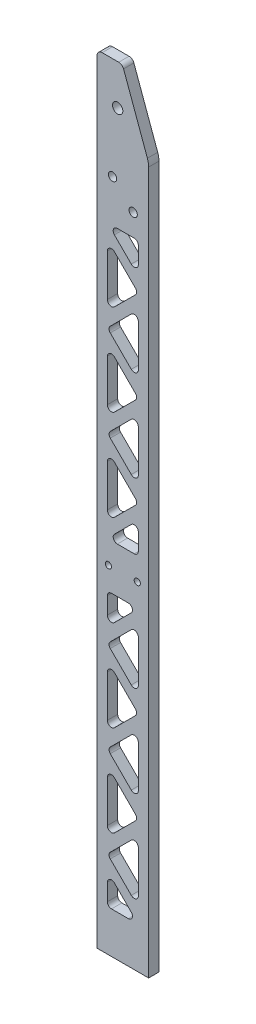
SolidWorks part; units mm, degrees
ref_plane "Plan de face" through (0, 0, 0) normal (0, 0, 1) x (1, 0, 0)
ref_plane "Plan de dessus" through (0, 0, 0) normal (0, 1, 0) x (1, 0, 0)
ref_plane "Plan de droite" through (0, 0, 0) normal (1, 0, 0) x (0, 0, -1)
sketch "Esquisse1" plane through (0, 0, 0) normal (0, 0, 1) x (1, 0, 0)
  line L1 (0, 0) -> (50, 0)
  line L2 (0, 0) -> (0, 594)
  line L3 (0, 594) -> (50, 594)
  line L4 (50, 0) -> (50, 594)
  dimension "D1" = 594
  dimension "D2" = 50
extrude "Boss.-Extru.1" add sketch "Esquisse1" along normal blind 10
sketch "Esquisse2" plane through (0, 0, 10) normal (0, 0, 1) x (1, 0, 0)
  line L0 (10, 10) -> (40, 10)
  line L1 (40, 10) -> (10, 40)
  line L2 (10, 40) -> (10, 10)
  line L3 (0, 0) -> (50, 0) construction
  line L4 (0, 594) -> (0, 0) construction
  line L5 (50, 0) -> (50, 594) construction
  line L6 (40, 24.1421) -> (10, 54.1421)
  line L11 (40, 84.1421) -> (40, 24.1421)
  line L12 (10, 54.1421) -> (40, 54.1421) construction
  line L13 (40, 84.1421) -> (10, 54.1421)
  line L14 (10, 68.2843) -> (10, 128.2843)
  line L15 (40, 98.2843) -> (10, 68.2843)
  line L16 (10, 98.2843) -> (40, 98.2843) construction
  line L17 (40, 98.2843) -> (10, 128.2843)
  line L18 (40, 172.4264) -> (10, 142.4264)
  line L19 (10, 156.5685) -> (10, 216.5685)
  line L20 (40, 186.5685) -> (10, 156.5685)
  line L21 (40, 186.5685) -> (10, 216.5685)
  line L22 (10, 142.4264) -> (40, 142.4264) construction
  line L23 (10, 186.5685) -> (40, 186.5685) construction
  line L24 (40, 172.4264) -> (40, 112.4264)
  line L25 (40, 112.4264) -> (10, 142.4264)
  line L26 (40, 260.7107) -> (10, 230.7107)
  line L28 (40, 274.8528) -> (10, 244.8528)
  line L30 (10, 230.7107) -> (40, 230.7107) construction
  line L31 (10, 274.8528) -> (40, 274.8528)
  line L32 (40, 260.7107) -> (40, 200.7107)
  line L33 (40, 200.7107) -> (10, 230.7107)
  line L34 (40, 348.9949) -> (10, 318.9949)
  line L35 (10, 333.1371) -> (10, 393.1371)
  line L36 (40, 363.1371) -> (10, 333.1371)
  line L37 (40, 363.1371) -> (10, 393.1371)
  line L38 (10, 318.9949) -> (40, 318.9949)
  line L39 (10, 363.1371) -> (40, 363.1371) construction
  line L42 (40, 437.2792) -> (10, 407.2792)
  line L43 (10, 421.4214) -> (10, 481.4214)
  line L44 (40, 451.4214) -> (10, 421.4214)
  line L45 (40, 451.4214) -> (10, 481.4214)
  line L46 (10, 407.2792) -> (40, 407.2792) construction
  line L47 (10, 451.4214) -> (40, 451.4214) construction
  line L48 (40, 437.2792) -> (40, 377.2792)
  line L49 (40, 377.2792) -> (10, 407.2792)
  line L50 (40, 525.5635) -> (10, 495.5635)
  line L51 (10, 509.7056) -> (10, 569.7056)
  line L52 (40, 539.7056) -> (10, 509.7056)
  line L53 (40, 539.7056) -> (10, 569.7056)
  line L54 (10, 495.5635) -> (40, 495.5635) construction
  line L55 (10, 539.7056) -> (40, 539.7056) construction
  line L56 (40, 525.5635) -> (40, 465.5635)
  line L57 (40, 465.5635) -> (10, 495.5635)
  line L62 (10, 583.8478) -> (40, 553.8478)
  line L63 (40, 553.8478) -> (40, 583.8478)
  line L70 (40, 583.8478) -> (10, 583.8478)
  line L71 (10, 244.8528) -> (10, 274.8528)
  line L74 (10, 128.2843) -> (10, 142.4264) construction
  line L75 (40, 98.2843) -> (40, 112.4264) construction
  line L76 (40, 348.9949) -> (40, 318.9949)
  line L77 (10, 244.8528) -> (10, 304.8528) [skipped]
  line L78 (40, 274.8528) -> (10, 304.8528) [skipped]
  line L79 (40, 288.9949) -> (10, 318.9949) [skipped]
  line L80 (40, 348.9949) -> (40, 288.9949) [skipped]
  dimension "D1" = 10
  dimension "D2" = 10
  dimension "D3" = 10
  dimension "D4" = 10
  dimension "D5" = 6
  dimension "D6" = 10
  dimension "D7" = 10
extrude "Enlèv. mat.-Extru.1" cut sketch "Esquisse2" against normal through all both and the other way through all
fillet "Congé1" radius 4 42 edges at (10, 128.2843, 5) (40, 98.2843, 5) (10, 68.2843, 5) (40, 24.1421, 5) (40, 84.1421, 5) (10, 54.1421, 5) (10, 40, 5) (40, 10, 5) (10, 10, 5) (10, 583.8478, 5) (40, 583.8478, 5) (40, 553.8478, 5) (10, 569.7056, 5) (40, 539.7056, 5) (10, 509.7056, 5) (40, 525.5635, 5) (10, 495.5635, 5) (40, 465.5635, 5) (40, 451.4214, 5) (10, 481.4214, 5) (10, 421.4214, 5) (40, 437.2792, 5) (40, 377.2792, 5) (10, 407.2792, 5) (40, 363.1371, 5) (10, 393.1371, 5) (10, 333.1371, 5) (40, 260.7107, 5) (10, 230.7107, 5) (40, 200.7107, 5) (10, 216.5685, 5) (40, 186.5685, 5) (10, 156.5685, 5) (40, 172.4264, 5) (10, 142.4264, 5) (40, 112.4264, 5) (10, 274.8528, 5) (10, 244.8528, 5) (40, 274.8528, 5) (40, 318.9949, 5) (40, 348.9949, 5) (10, 318.9949, 5)
sketch "Esquisse3" plane through (0, 0, 10) normal (0, 0, 1) x (1, 0, 0)
  line L0 (50, 0) -> (50, 594) construction
  line L1 (0, 0) -> (50, 0)
  line L2 (0, 0) -> (0, -30)
  line L3 (0, -30) -> (50, -30)
  line L4 (50, 0) -> (50, -30)
  dimension "D1" = 30
extrude "Boss.-Extru.2" add sketch "Esquisse3" against normal up to vertex (10 mm away) up to point (0, 0, 0)
sketch "Esquisse4" plane through (0, 0, 10) normal (0, 0, 1) x (1, 0, 0)
  line L0 (0, 296.9239) -> (50, 296.9239) construction
  line L1 (0, 594) -> (0, -30) construction
  line L2 (50, -30) -> (50, 594) construction
  line L3 (25, 274.8528) -> (25, 318.9949) construction
  line L4 (14, 274.8528) -> (30.3431, 274.8528) construction
  line L5 (36, 318.9949) -> (19.6569, 318.9949) construction
  circle A0 centre (39, 296.9239) radius 3
  circle A1 centre (11, 296.9239) radius 3
  point P14 (25, 296.9239)
  dimension "D1" = 6
  dimension "D2" = 28
extrude "Enlèv. mat.-Extru.2" cut sketch "Esquisse4" against normal through all both and the other way through all
sketch "Esquisse5" plane through (0, 0, 10) normal (0, 0, 1) x (1, 0, 0)
  line L5 (50, 594) -> (0, 594)
  line L6 (0, 594) -> (0, 724)
  line L7 (0, 724) -> (24.5221, 724)
  line L8 (24.5221, 724) -> (50, 654)
  line L9 (50, 654) -> (50, 594)
  dimension "D1" = 130
  dimension "D2" = 70
  dimension "D3" = 110
extrude "Boss.-Extru.3" add sketch "Esquisse5" against normal up to vertex (10 mm away) up to point (50, 594, 0)
sketch "Esquisse6" plane through (0, 0, 0) normal (0, 0, -1) x (-1, 0, 0)
  line L0 (-50, 605) -> (0, 605) construction
  line L1 (-50, -30) -> (-50, 654) construction
  line L2 (0, 724) -> (0, -30) construction
  line L3 (-50, 625) -> (0, 625) construction
  line L4 (0, -30) -> (-50, -30) construction
  circle A0 centre (-15, 625) radius 4
  circle A1 centre (-35, 605) radius 4
  circle A2 centre (-20, 685) radius 5
  dimension "D1" = 8
  dimension "D2" = 8
  dimension "D3" = 15
  dimension "D4" = 15
  dimension "D7" = 10
  dimension "D8" = 80
  dimension "D5" = 20
  dimension "D6" = 635
  dimension "D9" = 20
extrude "Enlèv. mat.-Extru.3" cut sketch "Esquisse6" against normal through all both and the other way through all
fillet "Congé2" radius 5 2 edges at (24.5221, 724, 5) (0, 724, 5)
fillet "Congé3" radius 20 1 edges at (50, 654, 5)
